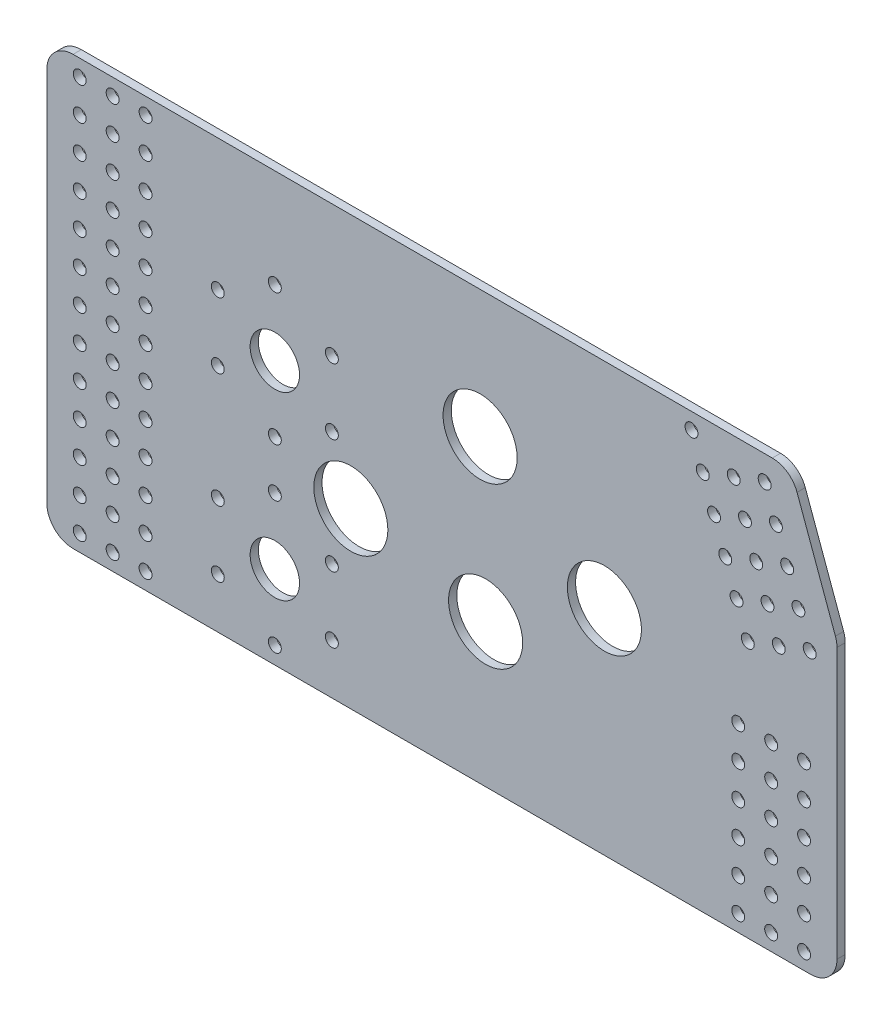
SolidWorks part; units mm, degrees
ref_plane "Front Plane" through (0, 0, 0) normal (0, 0, 1) x (1, 0, 0)
ref_plane "Top Plane" through (0, 0, 0) normal (0, 1, 0) x (1, 0, 0)
ref_plane "Right Plane" through (0, 0, 0) normal (1, 0, 0) x (0, 0, -1)
sketch "Sketch1" plane through (0, 0, 0) normal (0, 0, 1) x (1, 0, 0)
  line B0 (0, 0) -> (304.8, 0)
  line B1 (304.8, 0) -> (304.8, 116.0843)
  line B2 (304.8, 116.0843) -> (286.9597, 165.1)
  line B3 (286.9597, 165.1) -> (0, 165.1)
  line B4 (0, 165.1) -> (0, 0)
  line B5 (12.7, 158.75) -> (25.4, 158.75) construction
  line B6 (12.7, 158.75) -> (12.7, 146.05) construction
  line B7 (248.678, 158.8812) -> (253.0217, 146.9471) construction
  line B8 (266.7, 69.85) -> (266.7, 57.15) construction
  line B9 (87.9668, 101.6647) -> (87.9668, 127.0647) construction
  line B10 (87.9668, 32.0687) -> (87.9668, 6.6687) construction
  circle B11 centre (12.7, 158.75) radius 2.4892
  circle B12 centre (38.1, 6.35) radius 2.4892
  circle B13 centre (25.4, 158.75) radius 2.4892
  circle B14 centre (38.1, 158.75) radius 2.4892
  circle B15 centre (25.4, 146.05) radius 2.4892
  circle B16 centre (38.1, 146.05) radius 2.4892
  circle B17 centre (25.4, 133.35) radius 2.4892
  circle B18 centre (38.1, 133.35) radius 2.4892
  circle B19 centre (25.4, 120.65) radius 2.4892
  circle B20 centre (38.1, 120.65) radius 2.4892
  circle B21 centre (25.4, 107.95) radius 2.4892
  circle B22 centre (38.1, 107.95) radius 2.4892
  circle B23 centre (25.4, 95.25) radius 2.4892
  circle B24 centre (38.1, 95.25) radius 2.4892
  circle B25 centre (25.4, 82.55) radius 2.4892
  circle B26 centre (38.1, 82.55) radius 2.4892
  circle B27 centre (25.4, 69.85) radius 2.4892
  circle B28 centre (38.1, 69.85) radius 2.4892
  circle B29 centre (25.4, 57.15) radius 2.4892
  circle B30 centre (38.1, 57.15) radius 2.4892
  circle B31 centre (25.4, 44.45) radius 2.4892
  circle B32 centre (38.1, 44.45) radius 2.4892
  circle B33 centre (25.4, 31.75) radius 2.4892
  circle B34 centre (38.1, 31.75) radius 2.4892
  circle B35 centre (25.4, 19.05) radius 2.4892
  circle B36 centre (38.1, 19.05) radius 2.4892
  circle B37 centre (25.4, 6.35) radius 2.4892
  circle B38 centre (38.1, 6.35) radius 2.4892
  circle B39 centre (12.7, 146.05) radius 2.4892
  circle B40 centre (12.7, 133.35) radius 2.4892
  circle B41 centre (12.7, 120.65) radius 2.4892
  circle B42 centre (12.7, 107.95) radius 2.4892
  circle B43 centre (12.7, 95.25) radius 2.4892
  circle B44 centre (12.7, 82.55) radius 2.4892
  circle B45 centre (12.7, 69.85) radius 2.4892
  circle B46 centre (12.7, 57.15) radius 2.4892
  circle B47 centre (12.7, 44.45) radius 2.4892
  circle B48 centre (12.7, 31.75) radius 2.4892
  circle B49 centre (12.7, 19.05) radius 2.4892
  circle B50 centre (12.7, 6.35) radius 2.4892
  circle B51 centre (248.678, 158.8812) radius 2.4892
  circle B52 centre (264.9558, 151.2907) radius 2.4892
  circle B53 centre (276.8899, 155.6344) radius 2.4892
  circle B54 centre (253.0217, 146.9471) radius 2.4892
  circle B55 centre (269.2994, 139.3566) radius 2.4892
  circle B56 centre (281.2335, 143.7003) radius 2.4892
  circle B57 centre (257.3653, 135.013) radius 2.4892
  circle B58 centre (273.6431, 127.4226) radius 2.4892
  circle B59 centre (285.5772, 131.7662) radius 2.4892
  circle B60 centre (261.709, 123.0789) radius 2.4892
  circle B61 centre (277.9867, 115.4885) radius 2.4892
  circle B62 centre (289.9208, 119.8321) radius 2.4892
  circle B63 centre (266.0526, 111.1448) radius 2.4892
  circle B64 centre (282.3304, 103.5544) radius 2.4892
  circle B65 centre (294.2645, 107.898) radius 2.4892
  circle B66 centre (270.3963, 99.2107) radius 2.4892
  circle B67 centre (279.4, 69.85) radius 2.4892
  circle B68 centre (266.7, 69.85) radius 2.4892
  circle B69 centre (292.1, 69.85) radius 2.4892
  circle B70 centre (266.7, 57.15) radius 2.4892
  circle B71 centre (279.4, 57.15) radius 2.4892
  circle B72 centre (292.1, 57.15) radius 2.4892
  circle B73 centre (266.7, 44.45) radius 2.4892
  circle B74 centre (279.4, 44.45) radius 2.4892
  circle B75 centre (292.1, 44.45) radius 2.4892
  circle B76 centre (266.7, 31.75) radius 2.4892
  circle B77 centre (279.4, 31.75) radius 2.4892
  circle B78 centre (292.1, 31.75) radius 2.4892
  circle B79 centre (266.7, 19.05) radius 2.4892
  circle B80 centre (279.4, 19.05) radius 2.4892
  circle B81 centre (292.1, 19.05) radius 2.4892
  circle B82 centre (266.7, 6.35) radius 2.4892
  circle B83 centre (279.4, 6.35) radius 2.4892
  circle B84 centre (292.1, 6.35) radius 2.4892
  circle B85 centre (117.2755, 66.9374) radius 14.2875
  circle B86 centre (167.1476, 115.9152) radius 14.2875
  circle B87 centre (169.2697, 55.1778) radius 14.2875
  circle B88 centre (215.0818, 82.4983) radius 14.2875
  circle B89 centre (87.9668, 101.6647) radius 9.525
  circle B90 centre (87.9668, 32.0687) radius 9.525
  circle B91 centre (87.9668, 127.0647) radius 2.4892
  circle B92 centre (109.9639, 114.3647) radius 2.4892
  circle B93 centre (109.9639, 88.9647) radius 2.4892
  circle B94 centre (87.9668, 76.2647) radius 2.4892
  circle B95 centre (65.9698, 88.9647) radius 2.4892
  circle B96 centre (65.9698, 114.3647) radius 2.4892
  circle B97 centre (87.9668, 6.6687) radius 2.4892
  circle B98 centre (65.9698, 19.3687) radius 2.4892
  circle B99 centre (65.9698, 44.7687) radius 2.4892
  circle B100 centre (87.9668, 57.4687) radius 2.4892
  circle B101 centre (109.9639, 44.7687) radius 2.4892
  circle B102 centre (109.9639, 19.3687) radius 2.4892
sketch_block_instance "InsidePlateBLK-1"
sketch_block "InsidePlateBLK" parameters "D1"=4.9784, "D3"=4.9784, "D8"=4.9784, "D9"=4.9784, "D10"=4.9784, "D12"=4.9784, "D13"=4.9784, "D14"=4.9784, "D16"=19.05, "D17"=19.05, "D18"=28.575, "D19"=28.575, "D20"=28.575, "D21"=28.575, "D23"=4.9784, "D25"=4.9784, "D2"=6.35, "D4"=6.35, "D5"=12.7, "D6"=12.7, "D7"=12.7, "D11"=12.7, "D15"=12.7, "D22"=25.4, "D24"=25.4, "D26"=25.4, "D27"=25.4
extrude "Boss-Extrude1" add sketch "Sketch1" along normal blind 3.175 contours B3 B4 B0 B1 B2 B102 B101 B100 B99 B98 B97 B96 B95 B94 B93 B92 B91 B90 B89 B88 B87 B86 B85 B84 B83 B82 B81 B80
fillet "Fillet1" radius 10.16 5 edges at (0, 0, 1.5875) (304.8, 0, 1.5875) (304.8, 116.0843, 1.5875) (286.9597, 165.1, 1.5875) (0, 165.1, 1.5875)
